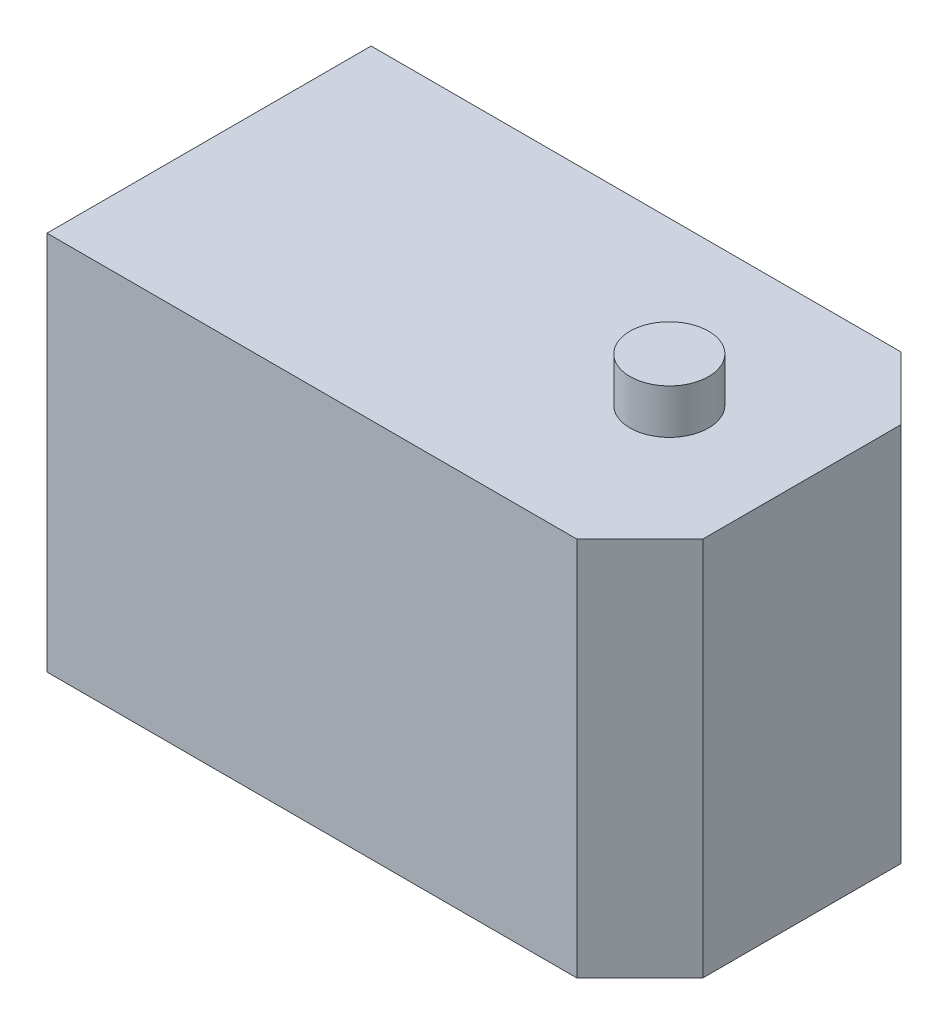
SolidWorks part; units mm, degrees
ref_plane "正面" through (0, 0, 0) normal (0, 0, 1) x (1, 0, 0)
ref_plane "平面" through (0, 0, 0) normal (0, 1, 0) x (1, 0, 0)
ref_plane "右側面" through (0, 0, 0) normal (1, 0, 0) x (0, 0, -1)
sketch "ｽｹｯﾁ1" plane through (0, 0, 0) normal (0, 1, 0) x (1, 0, 0)
  line L0 (-35.115, 0) -> (10.115, 0) construction
  line L1 (10.115, -12.365) -> (-35.115, -12.365)
  line L2 (10.115, -12.365) -> (10.115, 12.365)
  line L3 (10.115, 12.365) -> (-35.115, 12.365)
  line L4 (-35.115, -12.365) -> (-35.115, 12.365)
  line L5 (-12.5, 12.365) -> (-12.5, -12.365) construction
  circle A0 centre (0, 0) radius 3 construction
  dimension "D1" = 45.23
  dimension "D4" = 6
  dimension "D2" = 24.73
  dimension "D3" = 12.5
extrude "ﾎﾞｽ - 押し出し1" add sketch "ｽｹｯﾁ1" along normal blind 29
sketch "ｽｹｯﾁ2" plane through (0, 29, 0) normal (0, 1, 0) x (1, 0, 0)
  circle A0 centre (0, 0) radius 3
  dimension "D1" = 6
extrude "ﾎﾞｽ - 押し出し2" add sketch "ｽｹｯﾁ2" along normal blind 3.4
sketch "ｽｹｯﾁ3" plane through (0, 0, 0) normal (0, -1, 0) x (1, 0, 0)
  circle A0 centre (0, 0) radius 3
  dimension "D1" = 6
extrude "ﾎﾞｽ - 押し出し3" add sketch "ｽｹｯﾁ3" along normal blind 4.1
sketch "ｽｹｯﾁ4" plane through (0, 29, 0) normal (0, 1, 0) x (1, 0, 0)
  line L0 (5.3127, 12.365) -> (10.115, 12.365)
  line L1 (10.115, 12.365) -> (-35.115, 12.365) construction
  line L2 (10.115, 12.365) -> (10.115, 7.5627)
  line L3 (10.115, -12.365) -> (10.115, 12.365) construction
  line L4 (10.115, 7.5627) -> (5.3127, 12.365)
  line L5 (5.3127, -12.365) -> (10.115, -12.365)
  line L6 (-35.115, -12.365) -> (10.115, -12.365) construction
  line L7 (10.115, -12.365) -> (10.115, -7.5627)
  line L8 (10.115, -7.5627) -> (5.3127, -12.365)
  point P14 (4.7793, -12.365)
  dimension "D1" = 12.5
  dimension "D2" = 12.5
extrude "ｶｯﾄ - 押し出し1" cut sketch "ｽｹｯﾁ4" against normal through all
